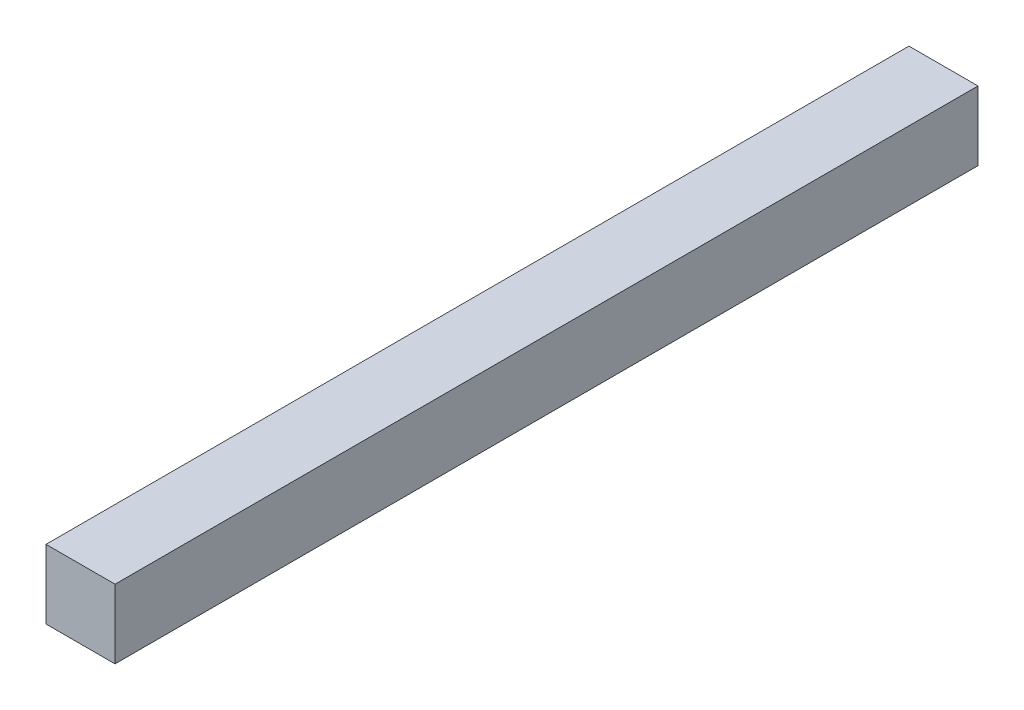
SolidWorks part; units mm, degrees
ref_plane "Front Plane" through (0, 0, 0) normal (0, 0, 1) x (1, 0, 0)
ref_plane "Top Plane" through (0, 0, 0) normal (0, 1, 0) x (1, 0, 0)
ref_plane "Right Plane" through (0, 0, 0) normal (1, 0, 0) x (0, 0, -1)
sketch "Sketch1" plane through (0, 0, 0) normal (0, 0, 1) x (1, 0, 0)
  line L0 (0, 40) -> (-40, 40)
  line L1 (-40, 40) -> (-40, -40)
  line L2 (-40, -40) -> (40, -40)
  line L3 (40, -40) -> (40, 0)
  line L4 (40, 0) -> (40, 40)
  line L5 (40, 40) -> (0, 40)
  dimension "D1" = 80
extrude "Boss-Extrude1" add sketch "Sketch1" along normal blind 1000
